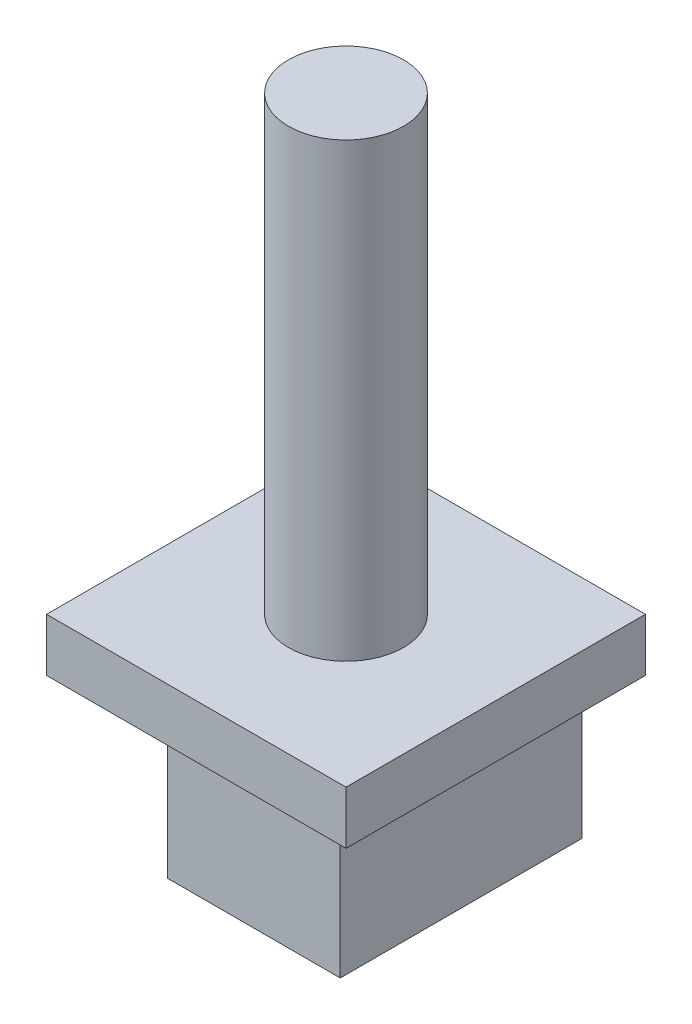
SolidWorks part; units mm, degrees
material "6061-T6 (SS)"
ref_plane "Front Plane" through (0, 0, 0) normal (0, 0, 1) x (1, 0, 0)
ref_plane "Top Plane" through (0, 0, 0) normal (0, 1, 0) x (1, 0, 0)
ref_plane "Right Plane" through (0, 0, 0) normal (1, 0, 0) x (0, 0, -1)
sketch "Sketch1" plane through (0, 0, 0) normal (0, 1, 0) x (1, 0, 0)
  circle A0 centre (0, 0) radius 6.35
  dimension "D1" = 12.7
extrude "Boss-Extrude1" add sketch "Sketch1" along normal blind 49.784
sketch "Sketch2" plane through (0, 0, 0) normal (0, -1, 0) x (1, 0, 0)
  line L1 (16.51, -16.51) -> (-16.51, -16.51)
  line L2 (16.51, -16.51) -> (16.51, 16.51)
  line L3 (16.51, 16.51) -> (-16.51, 16.51)
  line L4 (-16.51, -16.51) -> (-16.51, 16.51)
  line L5 (16.51, -16.51) -> (-16.51, 16.51) construction
  line L6 (16.51, 16.51) -> (-16.51, -16.51) construction
  point P0 (0, 0)
  dimension "D1" = 33.02
  dimension "D2" = 33.02
extrude "Boss-Extrude2" add sketch "Sketch2" along normal blind 5.842 contours L2 L3 L4 L1
sketch "Sketch3" plane through (0, -5.842, 0) normal (0, -1, 0) x (1, 0, 0)
  line L0 (-9.525, -16.51) -> (-9.525, 10.16)
  line L1 (16.51, -16.51) -> (-16.51, -16.51) construction
  line L2 (-9.525, 10.16) -> (9.525, 10.16)
  line L3 (9.525, 10.16) -> (9.525, -16.51)
  line L4 (-9.525, -16.51) -> (-16.51, -16.51) construction
  line L5 (9.525, -16.51) -> (16.51, -16.51) construction
  line L6 (-9.525, -16.51) -> (9.525, -16.51)
  line L10 (-16.51, -16.51) -> (16.51, -16.51)
  line L11 (16.51, -16.51) -> (16.51, 16.51)
  line L12 (16.51, 16.51) -> (-16.51, 16.51)
  line L13 (-16.51, 16.51) -> (-16.51, -16.51)
  line L14 (-9.525, -16.51) -> (16.51, -16.51) construction
  dimension "D1" = 26.67
  dimension "D2" = 19.05
  dimension "D3" = 0
extrude "Boss-Extrude3" add sketch "Sketch3" along normal blind 19.05 contours L2 L3 L6 L0
